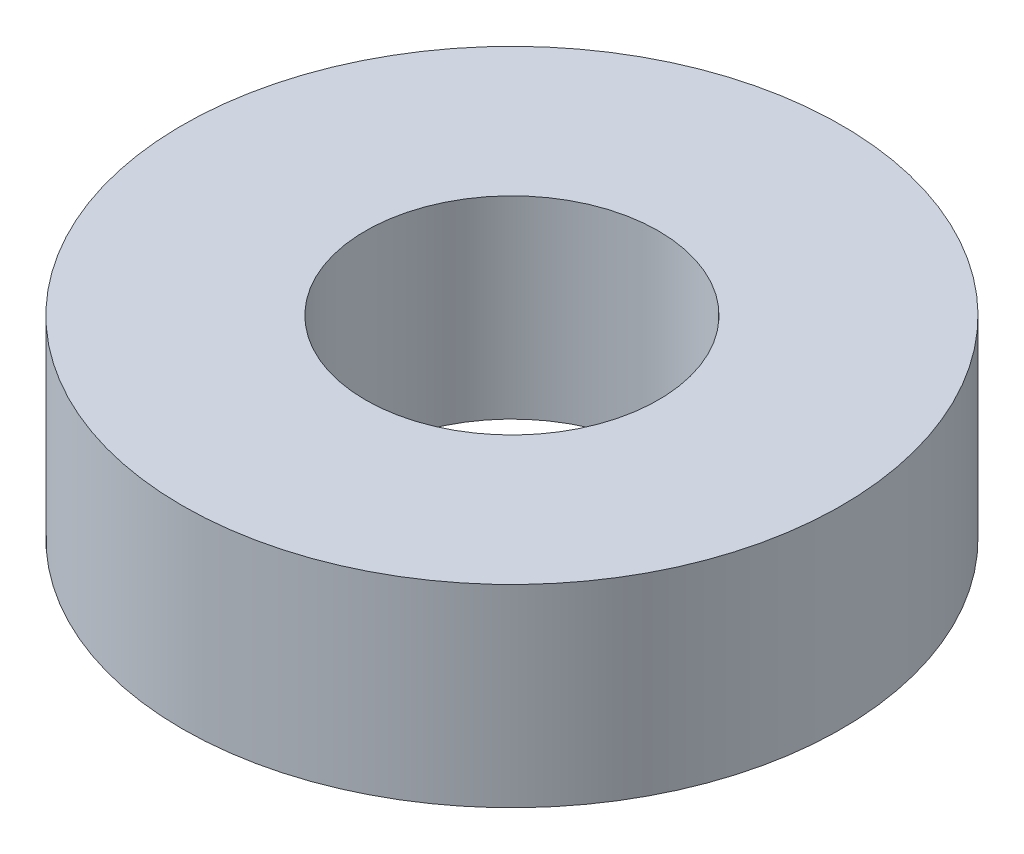
SolidWorks part; units mm, degrees
ref_plane "Front Plane" through (0, 0, 0) normal (0, 0, 1) x (1, 0, 0)
ref_plane "Top Plane" through (0, 0, 0) normal (0, 1, 0) x (1, 0, 0)
ref_plane "Right Plane" through (0, 0, 0) normal (1, 0, 0) x (0, 0, -1)
sketch "Sketch1" plane through (0, 0, 0) normal (0, 1, 0) x (1, 0, 0)
  circle A0 centre (-18.1561, 3.6585) radius 14.2875
  circle A2 centre (-18.1561, 3.6585) radius 6.35
  dimension "D1" = 28.575
  dimension "D2" = 12.7
extrude "Boss-Extrude3" add sketch "Sketch1" along normal blind 8.382 contours A2 | A0
